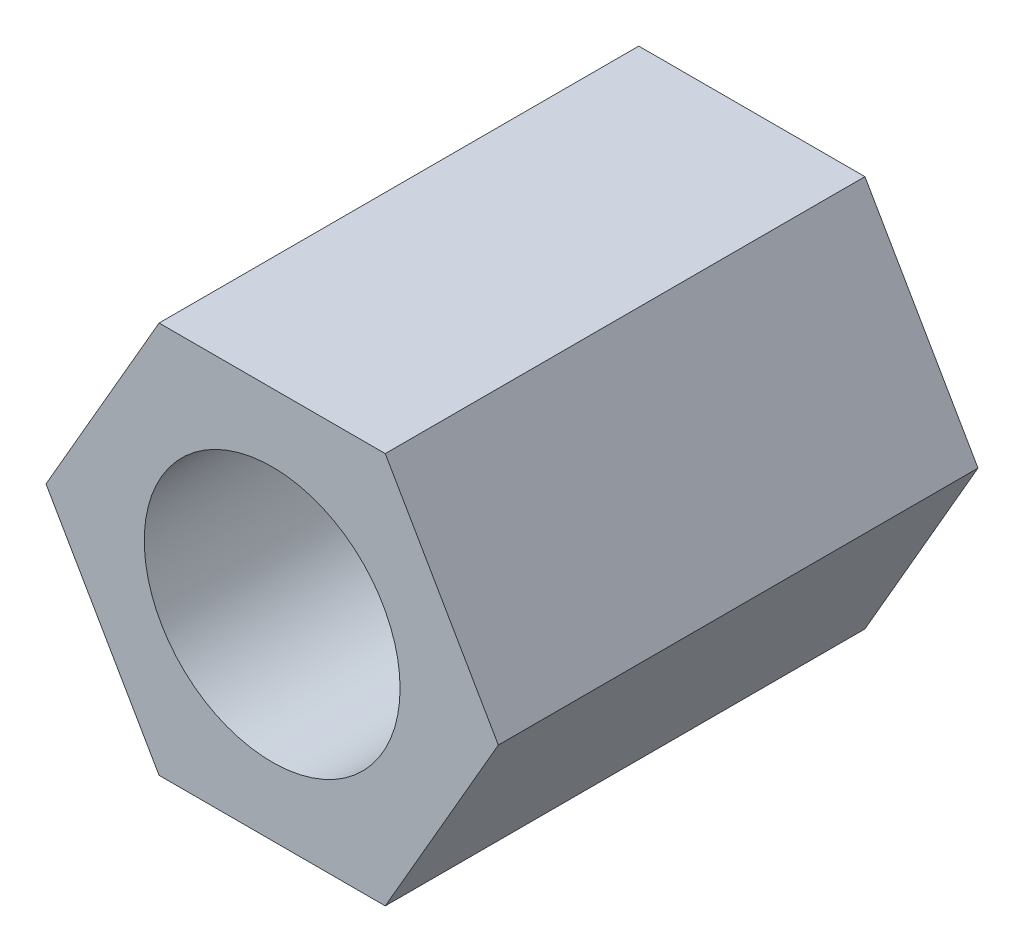
SolidWorks part; units mm, degrees
material "黄铜"
ref_plane "前视基准面" through (0, 0, 0) normal (0, 0, 1) x (1, 0, 0)
ref_plane "上视基准面" through (0, 0, 0) normal (0, 1, 0) x (1, 0, 0)
ref_plane "右视基准面" through (0, 0, 0) normal (1, 0, 0) x (0, 0, -1)
sketch "草图1" plane through (0, 0, 0) normal (0, 0, 1) x (1, 0, 0)
  line L1 (2.829, 0) -> (1.4145, 2.45)
  line L2 (1.4145, 2.45) -> (-1.4145, 2.45)
  line L3 (-1.4145, 2.45) -> (-2.829, 0)
  line L4 (-2.829, 0) -> (-1.4145, -2.45)
  line L5 (-1.4145, -2.45) -> (1.4145, -2.45)
  line L6 (1.4145, -2.45) -> (2.829, 0)
  circle A0 centre (0, 0) radius 1.6
  circle A1 centre (0, 0) radius 2.45 construction
  dimension "D1" = 3.2
  dimension "D2" = 4.9
extrude "凸台-拉伸1" add sketch "草图1" along normal blind 6
